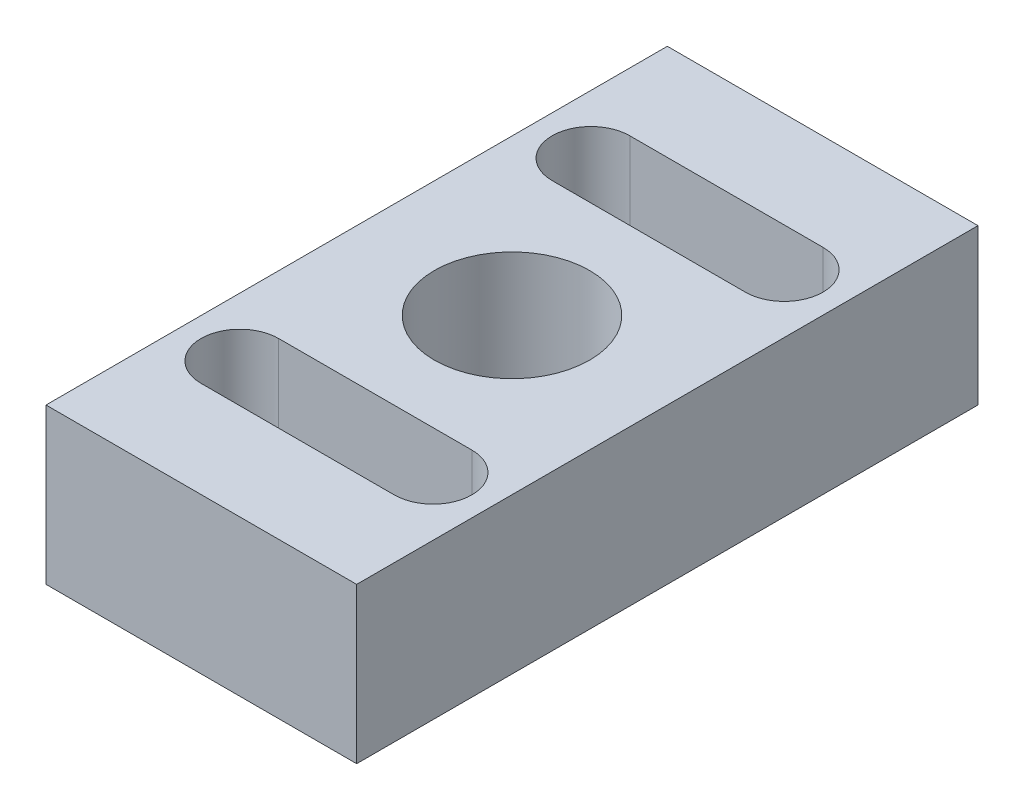
SolidWorks part; units mm, degrees
ref_plane "Front Plane" through (0, 0, 0) normal (0, 0, 1) x (1, 0, 0)
ref_plane "Top Plane" through (0, 0, 0) normal (0, 1, 0) x (1, 0, 0)
ref_plane "Right Plane" through (0, 0, 0) normal (1, 0, 0) x (0, 0, -1)
sketch "Sketch1" plane through (0, 0, 0) normal (0, 1, 0) x (1, 0, 0)
  line L1 (-6.35, -12.7) -> (6.35, -12.7)
  line L2 (-6.35, -12.7) -> (-6.35, 12.7)
  line L3 (-6.35, 12.7) -> (6.35, 12.7)
  line L4 (6.35, -12.7) -> (6.35, 12.7)
  line L5 (-6.35, -12.7) -> (6.35, 12.7) construction
  line L6 (-6.35, 12.7) -> (6.35, -12.7) construction
  point P0 (0, 0)
  dimension "D1" = 25.4
  dimension "D2" = 12.7
extrude "Boss-Extrude1" add sketch "Sketch1" along normal blind 6.35
sketch "Sketch2" plane through (0, 6.35, 0) normal (0, 1, 0) x (1, 0, 0)
  circle A0 centre (0, 0) radius 3.175
  dimension "D1" = 6.35
extrude "Cut-Extrude1" cut sketch "Sketch2" against normal through all
sketch "Sketch3" plane through (0, 6.35, 0) normal (0, 1, 0) x (1, 0, 0)
  line L0 (-3.9496, 7.1771) -> (3.9496, 7.1771) construction
  line L1 (-3.9496, 8.7646) -> (3.9496, 8.7646)
  line L2 (-3.9496, 5.5896) -> (3.9496, 5.5896)
  arc A0 (-3.9496, 8.7646) -> (-3.9496, 5.5896) centre (-3.9496, 7.1771) ccw
  arc A1 (3.9496, 5.5896) -> (3.9496, 8.7646) centre (3.9496, 7.1771) ccw
  point P2 (0, 7.1771)
  dimension "D1" = 1.5875
extrude "Cut-Extrude2" cut sketch "Sketch3" against normal through all
mirror "Mirror1" about plane through (0, 0, 0) normal (0, 0, 1) of "Cut-Extrude2"
